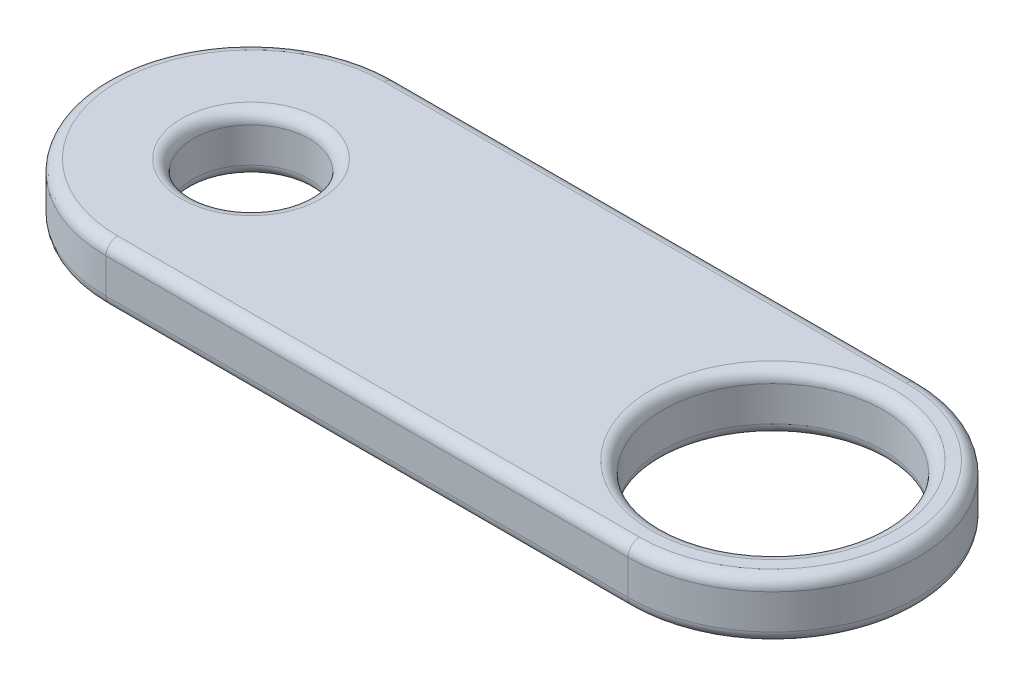
SolidWorks part; units mm, degrees
ref_plane "Front Plane" through (0, 0, 0) normal (0, 0, 1) x (1, 0, 0)
ref_plane "Top Plane" through (0, 0, 0) normal (0, 1, 0) x (1, 0, 0)
ref_plane "Right Plane" through (0, 0, 0) normal (1, 0, 0) x (0, 0, -1)
sketch "Sketch1" plane through (0, 0, 0) normal (0, 1, 0) x (1, 0, 0)
  line L0 (45, 12.5) -> (0, 12.5)
  line L1 (0, -12.5) -> (45, -12.5)
  arc A0 (0, 12.5) -> (0, -12.5) centre (0, 0) ccw
  arc A1 (45, -12.5) -> (45, 12.5) centre (45, 0) ccw
  circle A2 centre (0, 0) radius 5
  circle A3 centre (45, 0) radius 9.5
  dimension "D1" = 25
  dimension "D2" = 25
  dimension "D4" = 10
  dimension "D5" = 19
  dimension "D3" = 45
extrude "Boss-Extrude1" add sketch "Sketch1" along normal blind 5
ref_plane "Plane1" through (0, 2.5, 0) normal (0, 1, 0) x (1, 0, 0)
fillet "Fillet1" radius 1 12 edges at (45, 5, 9.5) (22.5, 5, 12.5) (-12.5, 5, 0) (22.5, 5, -12.5) (57.5, 5, 0) (0, 5, 5) (45, 0, 9.5) (0, 0, 5) (22.5, 0, -12.5) (-12.5, 0, 0) (22.5, 0, 12.5) (57.5, 0, 0)
